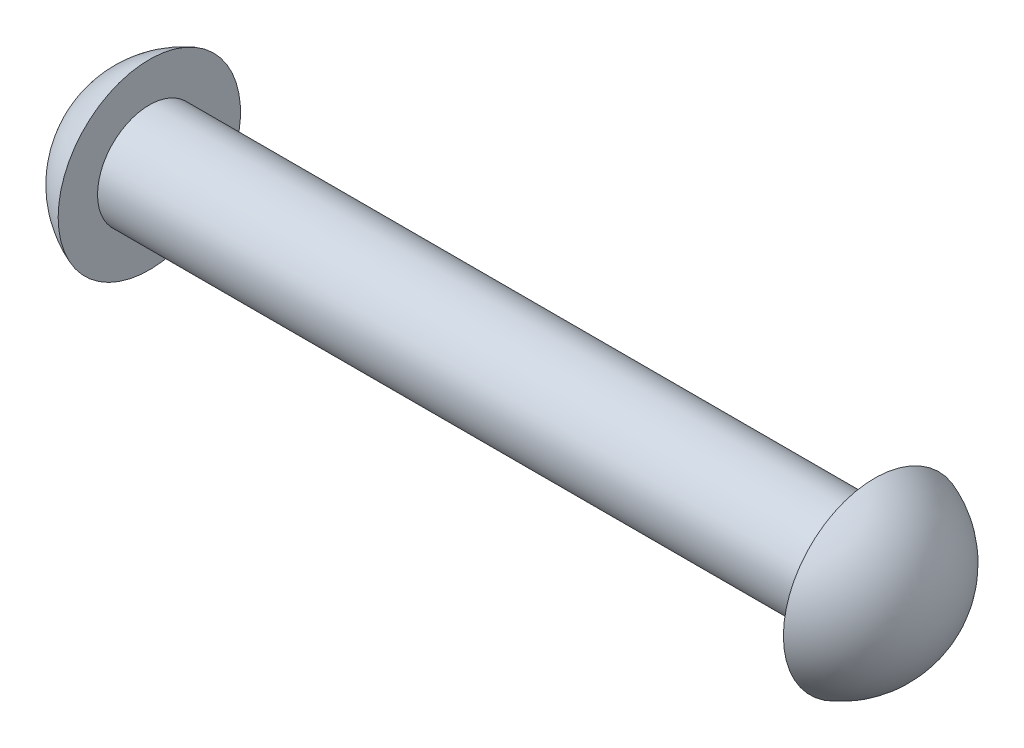
SolidWorks part; units mm, degrees
ref_plane "Plane1" through (0, 0, 0) normal (0, 0, 1) x (1, 0, 0)
ref_plane "Plane2" through (0, 0, 0) normal (0, 1, 0) x (1, 0, 0)
ref_plane "Plane3" through (0, 0, 0) normal (1, 0, 0) x (0, 0, -1)
sketch "Sketch1" plane through (0, 0, 0) normal (0, 0, 1) x (1, 0, 0)
  line L0 (-39, 0) -> (6, 0) construction
  line L1 (-38, 0) -> (0, 0)
  line L2 (-35, 2.5) -> (-35, 4.4)
  line L3 (-35, 2.5) -> (0, 2.5)
  line L4 (0, 2.5) -> (0, 0)
  arc A0 (-35, 4.4) -> (-38, 0) centre (-33.4008, 0.0869) ccw
  point P12 (-35, 2.5)
  dimension "HeadRadius" = 4.6
  dimension "Diameter" = 5
  dimension "GripLength" = 35
  dimension "HeadHt" = 3
  dimension "HeadDia" = 8.8
revolve "Base-Revolve" add sketch "Sketch1" angle 360 about L0
sketch "Sketch3" plane through (0, 0, 0) normal (0, 0, 1) x (1, 0, 0)
  line L0 (-49, 0) -> (71, 0) construction
  line L1 (0, 0) -> (3, 0)
  line L2 (0, 0) -> (0, 4.4)
  arc A0 (3, 0) -> (0, 4.4) centre (-1.5992, 0.0869) ccw
  dimension "D3" = 4.6
  dimension "D1" = 8.8
  dimension "D2" = 3
revolve "HeadTypeA" add sketch "Sketch3" angle 360 about L0
sketch "Sketch4" plane through (0, 0, 0) normal (0, 0, 1) x (1, 0, 0)
  line L0 (30, 0) -> (-54, 0) construction
  line L1 (-39, 0) -> (6, 0) construction
  line L2 (0, 0) -> (0, 4.4)
  line L3 (0, 4.4) -> (-2.4761, 2.5)
  line L4 (-2.4761, 0) -> (0, 0)
  line L5 (0, -4.4) -> (-2.4761, -2.5) construction
  line L6 (-2.4761, 0) -> (-2.4761, 2.5)
  dimension "D1" = 8.8
  dimension "D3" = 5
  dimension "D2" = 75
revolve "HeadTypeB" [suppressed] add sketch "Sketch4" angle 360 about L0
equation "\"D1@Sketch3\" = \"HeadDia@Sketch1\""
equation "\"D2@Sketch3\" = \"HeadHt@Sketch1\""
equation "\"D3@Sketch3\" = \"HeadRadius@Sketch1\""
equation "\"D1@Sketch4\" = \"HeadDia@Sketch1\""
equation "\"D3@Sketch4\" = \"Diameter@Sketch1\""
